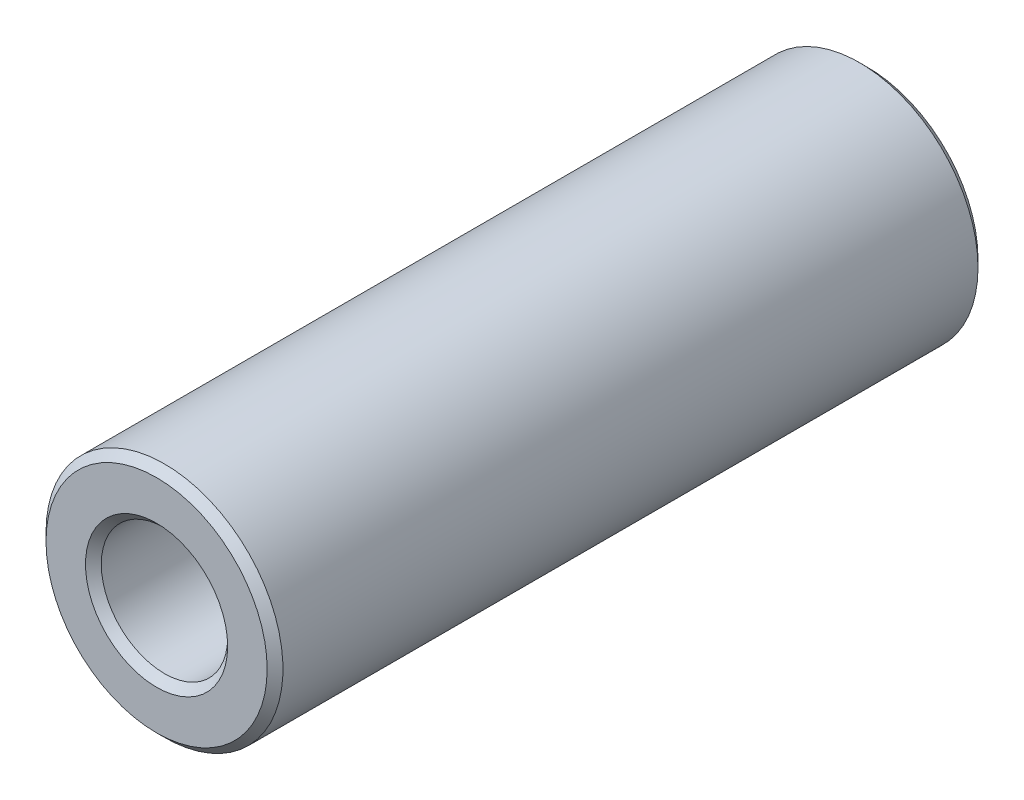
SolidWorks part; units mm, degrees
ref_plane "Спереди" through (0, 0, 0) normal (0, 0, 1) x (1, 0, 0)
ref_plane "Сверху" through (0, 0, 0) normal (0, 1, 0) x (1, 0, 0)
ref_plane "Справа" through (0, 0, 0) normal (1, 0, 0) x (0, 0, -1)
sketch "Эскиз1" plane through (0, 0, 0) normal (0, 0, 1) x (1, 0, 0)
  circle A0 centre (0, 0) radius 4
  circle A1 centre (0, 0) radius 7.5
extrude "Бобышка-Вытянуть1" add sketch "Эскиз1" along normal blind 45
chamfer "Фаска1" distance 0.5 angle 45 4 edges at (4, 0, 0) (7.5, 0, 0) (4, 0, 45) (7.5, 0, 45)
